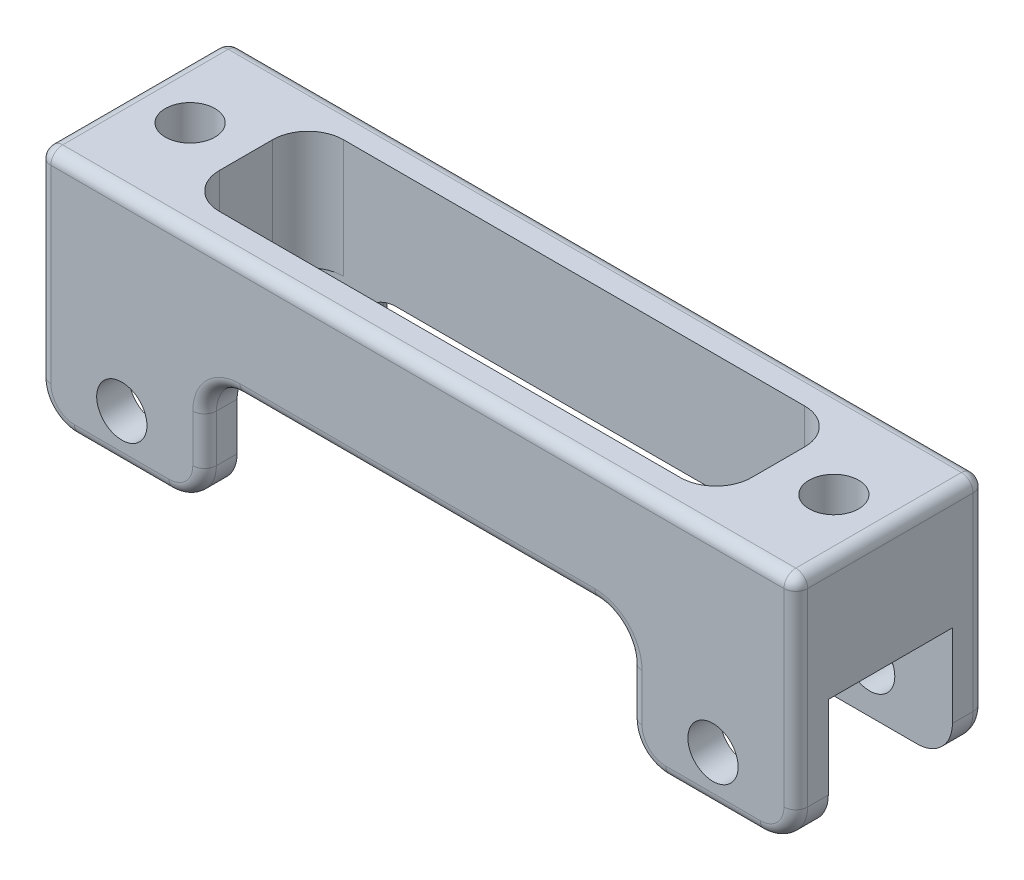
SolidWorks part; units mm, degrees
ref_plane "前视基准面" through (0, 0, 0) normal (0, 0, 1) x (1, 0, 0)
ref_plane "上视基准面" through (0, 0, 0) normal (0, 1, 0) x (1, 0, 0)
ref_plane "右视基准面" through (0, 0, 0) normal (1, 0, 0) x (0, 0, -1)
sketch "草图1" plane through (0, 0, 0) normal (0, 1, 0) x (1, 0, 0)
  line L1 (-32, 8) -> (32, 8)
  line L2 (-32, 8) -> (-32, -8)
  line L3 (-32, -8) -> (32, -8)
  line L4 (32, 8) -> (32, -8)
  line L5 (0, -8) -> (0, 8) construction
  line L6 (-32, 0) -> (32, 0) construction
  point P0 (0, 0)
  dimension "D1" = 64
  dimension "D2" = 16
extrude "凸台-拉伸1" add sketch "草图1" along normal blind 20
sketch "草图2" plane through (0, 20, 0) normal (0, 1, 0) x (1, 0, 0)
  line L0 (-43.8141, 0) -> (54.8834, 0) construction
  line L3 (0, 41.5129) -> (0, -54.4472) construction
  line L8 (-27.2236, 0) -> (27.2236, 0)
  line L9 (27.2236, 0) -> (27.2236, -54.4472)
  line L10 (27.2236, -54.4472) -> (-27.2236, -54.4472)
  line L11 (-27.2236, -54.4472) -> (-27.2236, 0)
  line L12 (-27.2236, 0) -> (27.2236, -54.4472)
  point P7 (0, 0)
  dimension "D1" = 45
  dimension "D2" = 77
sketch "草图3" plane through (0, 0, 8) normal (0, 0, 1) x (1, 0, 0)
  line L0 (0, 45.0356) -> (0, -25.3585) construction
  line L1 (-32, 10) -> (32, 10) construction
  line L2 (-32, 20) -> (-32, 0) construction
  line L3 (32, 20) -> (32, 0) construction
  line L4 (-32, 4) -> (32, 4) construction
  line L5 (-32, 0) -> (32, 0) construction
  circle A0 centre (-25, 4) radius 2.125
  circle A1 centre (25, 4) radius 2.125
  dimension "D2" = 4.25
  dimension "D3" = 50
  dimension "D1" = 4
extrude "切除-拉伸1" cut sketch "草图3" against normal blind 28
sketch "草图4" plane through (0, 0, 8) normal (0, 0, 1) x (1, 0, 0)
  line L0 (0, 23.7698) -> (0, -11.557) construction
  line L1 (-32, 0) -> (32, 0) construction
  line L2 (-18, 10) -> (18, 10)
  line L3 (-18, 10) -> (-18, 0)
  line L4 (-18, 0) -> (18, 0)
  line L5 (18, 10) -> (18, 0)
  line L6 (0, 0) -> (0, 10) construction
  line L7 (-18, 5) -> (18, 5) construction
  point P3 (0, 5)
  dimension "D1" = 10
  dimension "D2" = 36
extrude "切除-拉伸2" cut sketch "草图4" against normal blind 20
sketch "草图5" plane through (0, 0, 0) normal (0, -1, 0) x (1, 0, 0)
  line L0 (32, 8) -> (32, -8) construction
  line L1 (-32, 5.25) -> (32, 5.25)
  line L2 (-32, 5.25) -> (-32, -5.25)
  line L3 (-32, -5.25) -> (32, -5.25)
  line L4 (32, 5.25) -> (32, -5.25)
  line L5 (0, -5.25) -> (0, 5.25) construction
  line L6 (-32, 0) -> (32, 0) construction
  point P0 (0, 0)
  dimension "D1" = 10.5
extrude "切除-拉伸3" cut sketch "草图5" against normal blind 10
hole_wizard "M5 螺纹孔1" positions "3D草图1" profile "草图6" tap size "M5" standard "GB"
sketch3d "3D草图1"
  point P0 (-14.326, 10, -3.0431)
  point P1 (-27.2236, 20, 0)
  point P4 (27.2236, 20, 0)
sketch "草图6" plane through (27.2236, 20, 0) normal (1, 0, 0) x (0, 0, 1)
  line L0 (0, 0) -> (0, 13.6618)
  line L1 (0, 13.6618) -> (2.1, 12.4)
  line L2 (2.1, 12.4) -> (2.1, 0)
  line L5 (2.1, 0) -> (0, 0)
  line L10 (0, 13.6618) -> (-2.1, 12.4) construction
  line L11 (0, -6.35) -> (0, 107.95) construction
  dimension "螺纹孔钻头直径" = 4.2
  dimension "螺纹孔钻头深度" = 12.4
  dimension "导头角度" = 118
cosmetic thread "孔螺蚊线1" parameters "D1"=6, "D2"=5
cosmetic thread "孔螺蚊线2" parameters "D1"=6, "D2"=5
cosmetic thread "孔螺蚊线3" parameters "D1"=6, "D2"=5
fillet "圆角1" radius 3 8 edges at (32, 0, -6.625) (18, 0, -6.625) (32, 0, 6.625) (18, 0, 6.625) (-18, 0, -6.625) (-32, 0, -6.625) (-32, 0, 6.625) (-18, 0, 6.625)
fillet "圆角2" radius 3 4 edges at (18, 10, -6.625) (18, 10, 6.625) (-18, 10, -6.625) (-18, 10, 6.625)
sketch "草图7" plane through (0, 20, 0) normal (0, 1, 0) x (1, 0, 0)
  line L1 (-22.5, 5.25) -> (22.5, 5.25)
  line L2 (-22.5, 5.25) -> (-22.5, -5.25)
  line L3 (-22.5, -5.25) -> (22.5, -5.25)
  line L4 (22.5, 5.25) -> (22.5, -5.25)
  line L5 (0, -5.25) -> (0, 5.25) construction
  line L6 (-22.5, 0) -> (22.5, 0) construction
  point P0 (0, 0)
  dimension "D1" = 45
  dimension "D2" = 10.5
extrude "切除-拉伸4" cut sketch "草图7" against normal blind 10
fillet "圆角3" radius 3 4 edges at (22.5, 15, 5.25) (22.5, 15, -5.25) (-22.5, 15, 5.25) (-22.5, 15, -5.25)
fillet "圆角4" radius 1 30 edges at (-32, 11.5, 8) (-31.1213, 0.8787, 8) (-25, 0, 8) (-18.8787, 0.8787, 8) (-18, 5, 8) (-17.1213, 9.1213, 8) (0, 10, 8) (17.1213, 9.1213, 8) (18, 5, 8) (18.8787, 0.8787, 8) (25, 0, 8) (31.1213, 0.8787, 8) (-32, 11.5, -8) (-31.1213, 0.8787, -8) (-25, 0, -8) (-18.8787, 0.8787, -8) (-18, 5, -8) (-17.1213, 9.1213, -8) (0, 10, -8) (17.1213, 9.1213, -8) (18, 5, -8) (18.8787, 0.8787, -8) (25, 0, -8) (31.1213, 0.8787, -8) (-32, 20, 0) (0, 20, 8) (0, 20, -8) (32, 20, 0) (32, 11.5, 8) (32, 11.5, -8)
